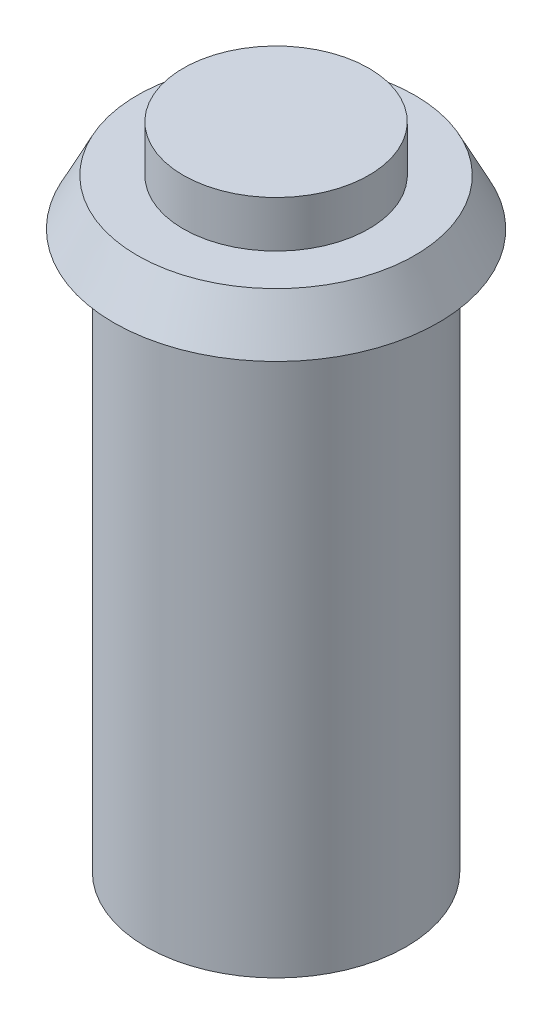
SolidWorks part; units mm, degrees
ref_plane "前视基准面" through (0, 0, 0) normal (0, 0, 1) x (1, 0, 0)
ref_plane "上视基准面" through (0, 0, 0) normal (0, 1, 0) x (1, 0, 0)
ref_plane "右视基准面" through (0, 0, 0) normal (1, 0, 0) x (0, 0, -1)
other "Configuration Table"
sketch "草图1" plane through (0, 0, 0) normal (0, 0, 1) x (1, 0, 0)
  line L0 (0, 55.9164) -> (0, -58.9254) construction
  line L1 (0, 28) -> (-4, 28)
  line L2 (-7, 24) -> (-5.9812, 26)
  line L3 (-7, 24) -> (-5.6, 24)
  line L4 (-5.6, 24) -> (-5.6, 0)
  line L5 (-5.6, 0) -> (0, 0)
  line L6 (-5.9812, 26) -> (-4, 26)
  line L7 (-4, 28) -> (-4, 26)
  line L8 (0, 28) -> (0, 0)
  point P5 (-5.9812, 26)
  dimension "D1" = 28
  dimension "D2" = 7
  dimension "D3" = 5.6
  dimension "D4" = 2
  dimension "D5" = 2
  dimension "D6" = 4
revolve "旋转1" add sketch "草图1" angle 360 about L0
